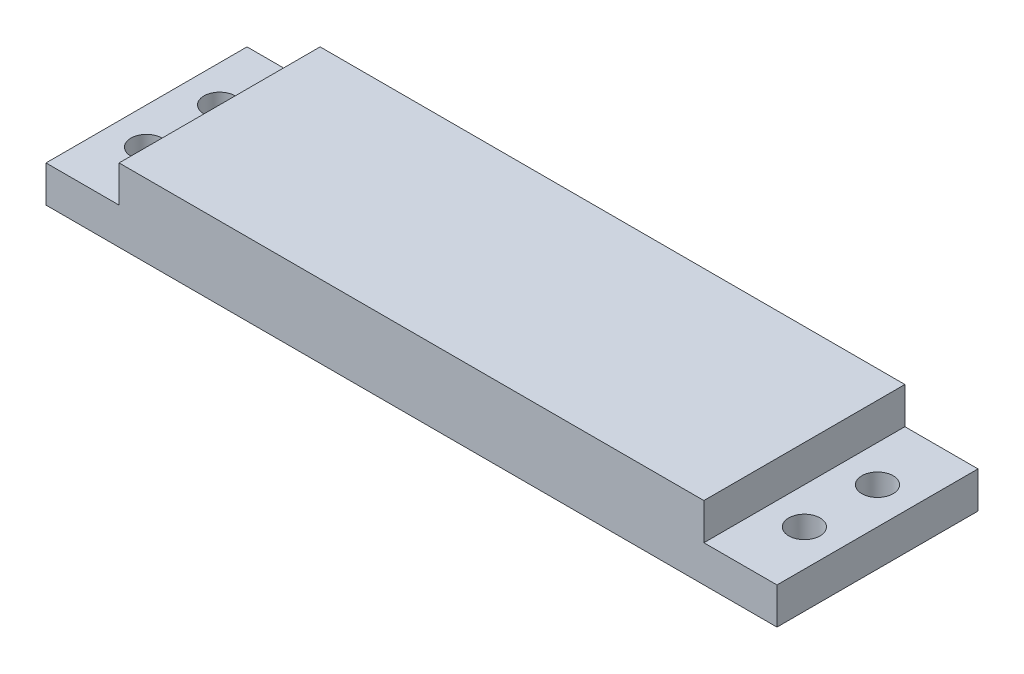
SolidWorks part; units mm, degrees
ref_plane "Front Plane" through (0, 0, 0) normal (0, 0, 1) x (1, 0, 0)
ref_plane "Top Plane" through (0, 0, 0) normal (0, 1, 0) x (1, 0, 0)
ref_plane "Right Plane" through (0, 0, 0) normal (1, 0, 0) x (0, 0, -1)
sketch "Sketch1" plane through (0, 0, 0) normal (0, 1, 0) x (1, 0, 0)
  line L1 (0, 0) -> (-63.5, 0)
  line L2 (0, 0) -> (0, 17.4625)
  line L3 (0, 17.4625) -> (-63.5, 17.4625)
  line L4 (-63.5, 0) -> (-63.5, 17.4625)
  dimension "D1" = 63.5
  dimension "D2" = 17.4625
extrude "Boss-Extrude1" add sketch "Sketch1" along normal blind 6.35
sketch "Sketch2" plane through (0, 0, 0) normal (0, 0, 1) x (1, 0, 0)
  line L0 (-31.75, 6.35) -> (-31.75, 0) construction
  line L1 (-63.5, 6.35) -> (0, 6.35) construction
  line L2 (-63.5, 0) -> (0, 0) construction
  line L3 (-6.35, 6.35) -> (-6.35, 3.175)
  line L4 (-63.5, 6.35) -> (-57.15, 6.35)
  line L5 (-63.5, 6.35) -> (-63.5, 3.175)
  line L6 (-63.5, 3.175) -> (-57.15, 3.175)
  line L7 (-57.15, 6.35) -> (-57.15, 3.175)
  line L8 (0, 3.175) -> (-6.35, 3.175)
  line L9 (0, 6.35) -> (0, 3.175)
  line L10 (0, 6.35) -> (-6.35, 6.35)
  dimension "D1" = 6.35
  dimension "D2" = 3.175
extrude "Cut-Extrude1" cut sketch "Sketch2" against normal through all
sketch "Sketch3" plane through (0, 6.35, 0) normal (0, 1, 0) x (1, 0, 0)
  line L0 (-63.5, 8.7312) -> (0, 8.7312) construction
  line L1 (-63.5, 17.4625) -> (-63.5, 0) construction
  line L2 (0, 17.4625) -> (0, 0) construction
  line L3 (-60.325, 17.4625) -> (-60.325, 0) construction
  line L4 (-63.5, 17.4625) -> (-57.15, 17.4625) construction
  line L5 (-63.5, 0) -> (-57.15, 0) construction
  line L6 (-31.75, 17.4625) -> (-31.75, 0) construction
  line L7 (-6.35, 17.4625) -> (-57.15, 17.4625) construction
  line L8 (-57.15, 0) -> (-6.35, 0) construction
  line L9 (-3.175, 17.4625) -> (-3.175, 0) construction
  circle A0 centre (-60.325, 11.9062) radius 1.3579
  circle A1 centre (-60.325, 5.5562) radius 1.3579
  circle A2 centre (-3.175, 5.5562) radius 1.3579
  circle A3 centre (-3.175, 11.9063) radius 1.3579
  dimension "D1" = 3.175
extrude "Cut-Extrude2" cut sketch "Sketch3" against normal through all
